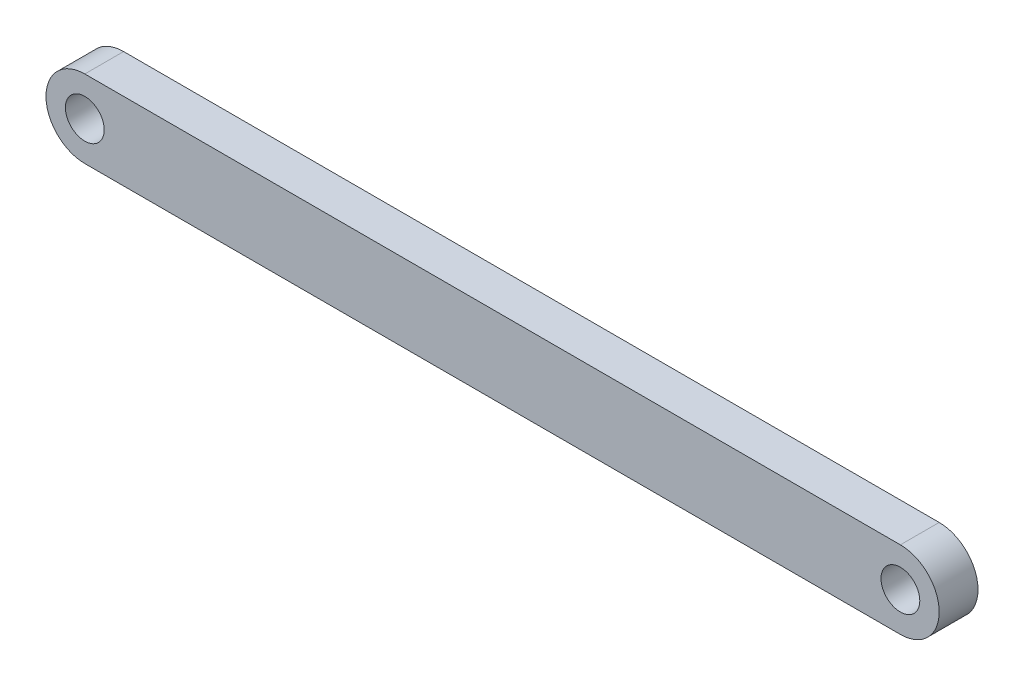
SolidWorks part; units mm, degrees
ref_plane "Plano frontal" through (0, 0, 0) normal (0, 0, 1) x (1, 0, 0)
ref_plane "Plano superior" through (0, 0, 0) normal (0, 1, 0) x (1, 0, 0)
ref_plane "Plano direito" through (0, 0, 0) normal (1, 0, 0) x (0, 0, -1)
sketch "Esboço1" plane through (0, 0, 0) normal (0, 0, 1) x (1, 0, 0)
  line L0 (-52.54, 5) -> (52.54, 5)
  line L1 (-11.6732, 0) -> (11.6732, 0) construction
  line L2 (-52.54, -5) -> (52.54, -5)
  arc A0 (-52.54, 5) -> (-52.54, -5) centre (-52.54, 0) ccw
  arc A1 (52.54, 5) -> (52.54, -5) centre (52.54, 0) cw
  circle A2 centre (-52.54, 0) radius 2.5
  circle A3 centre (52.54, 0) radius 2.5
  point P3 (0, 5)
  dimension "D1" = 10
  dimension "D2" = 105.08
extrude "Ressalto-extrusão1" add sketch "Esboço1" along normal blind 5
